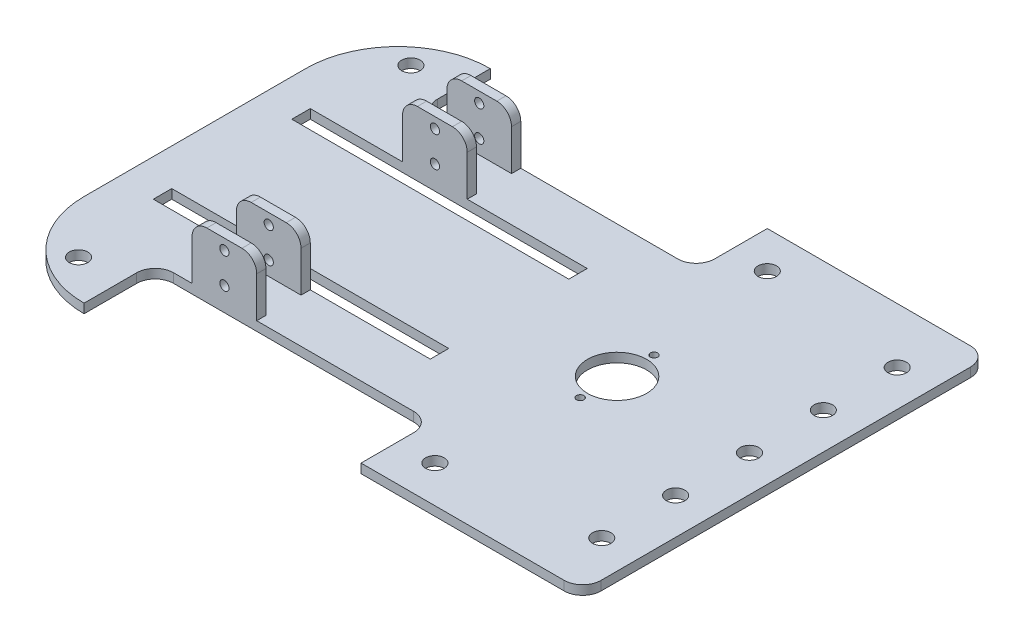
SolidWorks part; units mm, degrees
ref_plane "Front Plane" through (0, 0, 0) normal (0, 0, 1) x (1, 0, 0)
ref_plane "Top Plane" through (0, 0, 0) normal (0, 1, 0) x (1, 0, 0)
ref_plane "Right Plane" through (0, 0, 0) normal (1, 0, 0) x (0, 0, -1)
sketch "Sketch1" plane through (0, 0, 0) normal (0, 1, 0) x (1, 0, 0)
  line L1 (-160, 110) -> (160, 110)
  line L2 (-160, 110) -> (-160, -110)
  line L3 (-160, -110) -> (160, -110)
  line L4 (160, 110) -> (160, -110)
  line L5 (-160, 110) -> (160, -110) construction
  line L6 (-160, -110) -> (160, 110) construction
  point P1 (0, 0)
  dimension "D1" = 320
  dimension "D2" = 220
extrude "Boss-Extrude1" add sketch "Sketch1" along normal mid plane 5
sketch "Sketch2" plane through (0, 0, 0) normal (0, 1, 0) x (1, 0, 0)
  line L0 (0, 110) -> (0, -110) construction
  line L1 (160, 110) -> (-160, 110) construction
  line L2 (-160, -110) -> (160, -110) construction
  line L3 (160, 0) -> (-160, 0) construction
  line L4 (160, -110) -> (160, 110) construction
  line L5 (-160, 110) -> (-160, -110) construction
  line L6 (-133, 90) -> (-133, 0) construction
  line L7 (-133, -90) -> (-133, 0) construction
  line L8 (-160, 110) -> (-160, -110) construction
  line L10 (60, 90) -> (60, -90) construction
  line L11 (160, -110) -> (160, 110) construction
  circle A0 centre (-133, 90) radius 5
  circle A1 centre (-133, -90) radius 5
  circle A2 centre (60, 90) radius 5
  circle A3 centre (60, -90) radius 5
  dimension "D2" = 10
  dimension "D3" = 10
  dimension "D5" = 10
  dimension "D6" = 10
  dimension "D1" = 20
  dimension "D4" = 27
  dimension "D7" = 100
extrude "Cut-Extrude1" cut sketch "Sketch2" along direction (0, 1, 0) on the side against the normal mid plane 5
fillet "Fillet5" radius 50 2 edges at (-160, 0, -110) (-160, 0, 110)
sketch "Sketch3" plane through (0, 0, 0) normal (0, 1, 0) x (1, 0, 0)
  line L0 (160, 0) -> (-160, 0) construction
  line L1 (160, -110) -> (160, 110) construction
  line L2 (-160, 60) -> (-160, -60) construction
  line L3 (-110, 110) -> (-110, 71.5023)
  line L4 (160, 110) -> (-110, 110) construction
  line L5 (-110, 71.5023) -> (40, 71.5023)
  line L6 (40, 71.5023) -> (40, 110)
  line L7 (40, 110) -> (-110, 110)
  line L8 (40, -71.5023) -> (40, -110)
  line L9 (-110, -110) -> (-110, -71.5023)
  line L10 (-110, -71.5023) -> (40, -71.5023)
  line L11 (40, -110) -> (-110, -110)
  dimension "D1" = 150
  dimension "D2" = 50
extrude "Cut-Extrude2" cut sketch "Sketch3" against normal mid plane 5
fillet "Fillet3" radius 10 4 edges at (40, 0, 71.5023) (-110, 0, 71.5023) (-110, 0, -71.5023) (40, 0, -71.5023)
sketch "Sketch4" plane through (0, 0, 0) normal (0, 1, 0) x (1, 0, 0)
  line L0 (160, 0) -> (-160, 0) construction
  line L1 (160, -110) -> (160, 110) construction
  line L2 (-160, 60) -> (-160, -60) construction
  line L6 (68.6574, 20) -> (68.6574, 0) construction
  line L7 (68.6574, 0) -> (68.6574, -20) construction
  circle A0 centre (68.6574, 0) radius 16
  circle A1 centre (68.6574, 20) radius 2
  circle A2 centre (68.6574, -20) radius 2
  dimension "D1" = 32
  dimension "D2" = 2
  dimension "D3" = 4
  dimension "D4" = 40
extrude "Cut-Extrude3" cut sketch "Sketch4" against normal mid plane 5
sketch "Sketch6" plane through (0, 0, 0) normal (0, 1, 0) x (1, 0, 0)
  line L0 (160, 0) -> (-160, 0) construction
  line L1 (160, -110) -> (160, 110) construction
  line L2 (-160, 60) -> (-160, -60) construction
  circle A0 centre (140.3612, 0) radius 5
  dimension "D1" = 10
extrude "Cut-Extrude4" cut sketch "Sketch6" against normal mid plane 5
pattern_linear "LPattern1" count 3 spacing 40 along (0, 0, -1) of "Cut-Extrude4"
pattern_linear "LPattern2" count 3 spacing 40 along (0, 0, 1) of "Cut-Extrude4"
sketch "Sketch8" plane through (0, 2.5, 0) normal (0, 1, 0) x (1, 0, 0)
  line L0 (30, -71.5023) -> (-100, -71.5023) construction
  line L1 (-90, -71.5023) -> (-55, -71.5023)
  line L2 (-90, -71.5023) -> (-90, -66.5023)
  line L3 (-90, -66.5023) -> (-55, -66.5023)
  line L4 (-55, -71.5023) -> (-55, -66.5023)
  line L5 (-110, -81.5023) -> (-110, -110) construction
  line L6 (160, 0) -> (-160, 0) construction
  line L7 (160, -110) -> (160, 110) construction
  line L8 (-160, 60) -> (-160, -60) construction
  line L13 (-160, -47.5023) -> (160, -47.5023) construction
  line L14 (160, -110) -> (160, 110) construction
  line L15 (-72.5, -66.5023) -> (-72.5, -47.5023) construction
  line L16 (-72.5, -57.0023) -> (-160, -57.0023) construction
  line L17 (-55, -42.5023) -> (-55, -47.5023)
  line L18 (-90, -47.5023) -> (-55, -47.5023)
  line L19 (-90, -42.5023) -> (-90, -47.5023)
  line L20 (-90, -42.5023) -> (-55, -42.5023)
  line L21 (-72.5, 57.0023) -> (-160, 57.0023) construction
  line L22 (-72.5, 66.5023) -> (-72.5, 47.5023) construction
  line L23 (-160, 47.5023) -> (160, 47.5023) construction
  line L24 (-90, 42.5023) -> (-55, 42.5023)
  line L25 (-90, 42.5023) -> (-90, 47.5023)
  line L26 (-90, 47.5023) -> (-55, 47.5023)
  line L27 (-55, 42.5023) -> (-55, 47.5023)
  line L28 (-55, 71.5023) -> (-55, 66.5023)
  line L29 (-90, 66.5023) -> (-55, 66.5023)
  line L30 (-90, 71.5023) -> (-90, 66.5023)
  line L31 (-90, 71.5023) -> (-55, 71.5023)
  point P22 (-72.5, -66.5023)
  dimension "D1" = 5
  dimension "D2" = 20
  dimension "D3" = 35
  dimension "D4" = 19
extrude "Boss-Extrude2" add sketch "Sketch8" along normal blind 30
sketch "Sketch9" plane through (0, 0, 71.5023) normal (0, 0, 1) x (1, 0, 0)
  line L0 (-72.5, 32.5) -> (-72.5, -2.5) construction
  line L1 (-90, 32.5) -> (-55, 32.5) construction
  line L2 (30, -2.5) -> (-100, -2.5) construction
  circle A0 centre (-72.5, 26.7448) radius 2.5
  circle A1 centre (-72.5, 10.2508) radius 2.5
  dimension "D1" = 5
  dimension "D2" = 5
extrude "Cut-Extrude5" cut sketch "Sketch9" against normal up to surface (143.0046 mm away)
fillet "Fillet6" radius 8 8 edges at (-90, 32.5, 69.0023) (-55, 32.5, 69.0023) (-55, 32.5, -69.0023) (-90, 32.5, -69.0023) (-90, 32.5, -45.0023) (-55, 32.5, -45.0023) (-55, 32.5, 45.0023) (-90, 32.5, 45.0023)
sketch "Sketch10" plane through (0, 0, 0) normal (0, 1, 0) x (1, 0, 0)
  line L1 (-140, -32.5023) -> (10, -32.5023)
  line L2 (-140, -32.5023) -> (-140, -42.5023)
  line L3 (-140, -42.5023) -> (10, -42.5023)
  line L4 (10, -32.5023) -> (10, -42.5023)
  line L5 (-160, 60) -> (-160, -60) construction
  line L6 (-160, 0) -> (160, 0) construction
  line L7 (160, -110) -> (160, 110) construction
  line L8 (10, 32.5023) -> (10, 42.5023)
  line L9 (-140, 42.5023) -> (10, 42.5023)
  line L10 (-140, 32.5023) -> (-140, 42.5023)
  line L11 (-140, 32.5023) -> (10, 32.5023)
  line L12 (-55, -42.5023) -> (-90, -42.5023) construction
  dimension "D2" = 20
  dimension "D3" = 150
  dimension "D4" = 10
extrude "Cut-Extrude6" cut sketch "Sketch10" against normal mid plane 67.5
fillet "Fillet7" radius 10 2 edges at (160, 0, 110) (160, 0, -110)
equation "\"carW\"= 22cm"
equation "\"carL\"= 32cm"
equation "\"D1@Sketch1\"=\"carL\""
equation "\"D2@Sketch1\"=\"carW\""
equation "\"carT\"= .5cm'car thickness"
equation "\"D1@Boss-Extrude1\"=\"carT\""
equation "\"linkNialDim\"= 10mm"
equation "\"D2@Sketch2\"=\"linkNialDim\""
equation "\"D3@Sketch2\"=\"linkNialDim\""
equation "\"D1@Sketch8\"=\"carT\""
equation "\"D5@Sketch2\"=\"linkNialDim\""
equation "\"D6@Sketch2\"=\"linkNialDim\""
